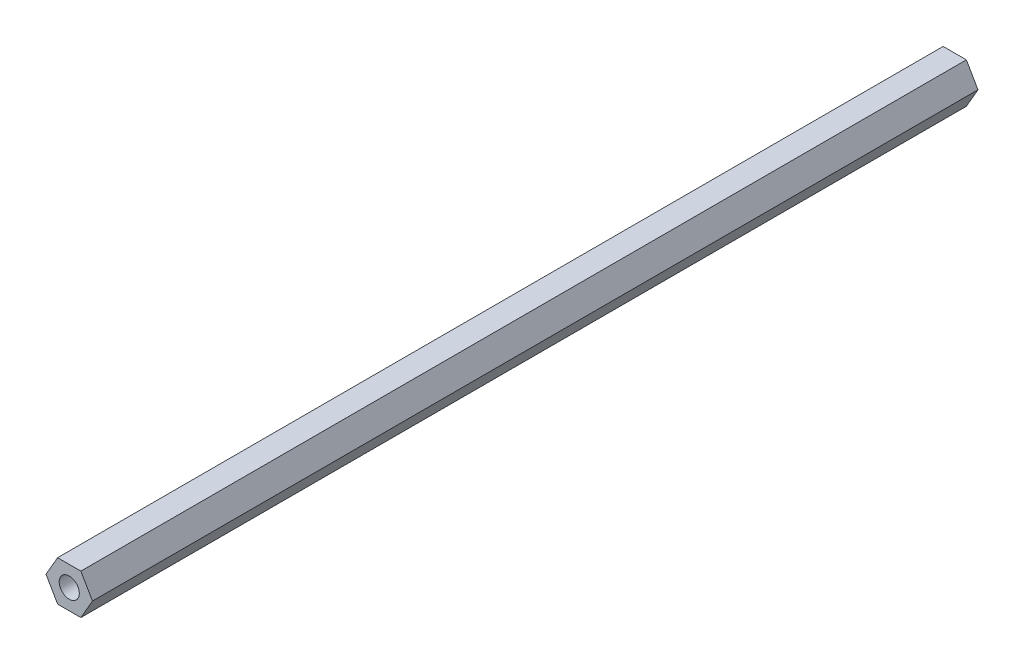
SolidWorks part; units mm, degrees
ref_plane "Front Plane" through (0, 0, 0) normal (0, 0, 1) x (1, 0, 0)
ref_plane "Top Plane" through (0, 0, 0) normal (0, 1, 0) x (1, 0, 0)
ref_plane "Right Plane" through (0, 0, 0) normal (1, 0, 0) x (0, 0, -1)
sketch "Sketch1" plane through (0, 0, 0) normal (0, 0, 1) x (1, 0, 0)
  line L1 (-7.3323, 0) -> (-3.6662, -6.35)
  line L2 (-3.6662, -6.35) -> (3.6662, -6.35)
  line L3 (3.6662, -6.35) -> (7.3323, 0)
  line L4 (7.3323, 0) -> (3.6662, 6.35)
  line L5 (3.6662, 6.35) -> (-3.6662, 6.35)
  line L6 (-3.6662, 6.35) -> (-7.3323, 0)
  circle A0 centre (0, 0) radius 6.35 construction
  circle A1 centre (0, 0) radius 3.175
  dimension "D2" = 6.35
  dimension "D1" = 12.7
extrude "Boss-Extrude1" add sketch "Sketch1" along normal blind 279.4
